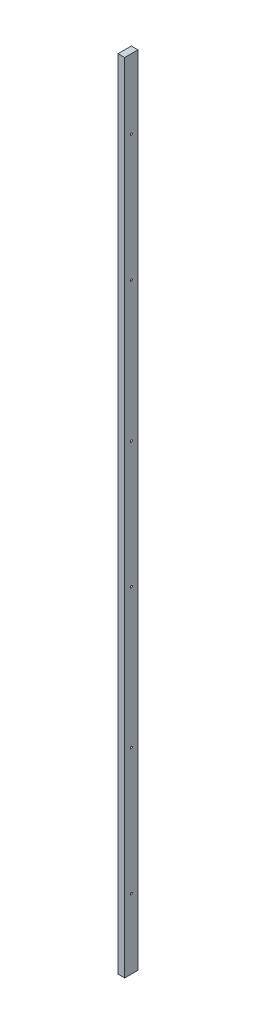
SolidWorks part; units mm, degrees
ref_plane "Спереди" through (0, 0, 0) normal (0, 0, 1) x (1, 0, 0)
ref_plane "Сверху" through (0, 0, 0) normal (0, 1, 0) x (1, 0, 0)
ref_plane "Справа" through (0, 0, 0) normal (1, 0, 0) x (0, 0, -1)
other "Configuration Table"
sketch "Эскиз1" plane through (0, 0, 0) normal (0, 1, 0) x (1, 0, 0)
  line L1 (12.5, 25) -> (-12.5, 25)
  line L2 (12.5, 25) -> (12.5, -25)
  line L3 (12.5, -25) -> (-12.5, -25)
  line L4 (-12.5, 25) -> (-12.5, -25)
  line L5 (12.5, 25) -> (-12.5, -25) construction
  line L6 (12.5, -25) -> (-12.5, 25) construction
  point P0 (0, 0)
extrude "Бобышка-Вытянуть1" add sketch "Эскиз1" along normal blind 3000
sketch "Эскиз2" plane through (12.5, 0, 0) normal (1, 0, 0) x (0, 0, -1)
  line L0 (0, 3000) -> (0, 2737.5) construction
  line L1 (-25, 3000) -> (25, 3000) construction
  line L2 (0, 0) -> (0, 262.5) construction
  line L3 (0, 262.5) -> (0, 737.5) construction
  circle A0 centre (0, 2737.5) radius 4
  circle A1 centre (0, 262.5) radius 4
  circle A2 centre (0, 737.5) radius 4
extrude "Вырез-Вытянуть1" cut sketch "Эскиз2" against normal blind 3000
sketch "Эскиз3" plane through (-12.5, 0, 0) normal (-1, 0, 0) x (0, 0, 1)
  line L0 (0, 2737.5) -> (0, 2262.5) construction
  circle A0 centre (0, 2262.5) radius 4
extrude "Вырез-Вытянуть2" cut sketch "Эскиз3" against normal blind 3000
sketch "Эскиз4" plane through (-12.5, 0, 0) normal (-1, 0, 0) x (0, 0, 1)
  line L0 (0, 2262.5) -> (0, 1737.5) construction
  line L1 (0, 737.5) -> (0, 1262.5) construction
  circle A0 centre (0, 1737.5) radius 4
  circle A1 centre (0, 1262.5) radius 4
extrude "Вырез-Вытянуть3" cut sketch "Эскиз4" against normal blind 3000
